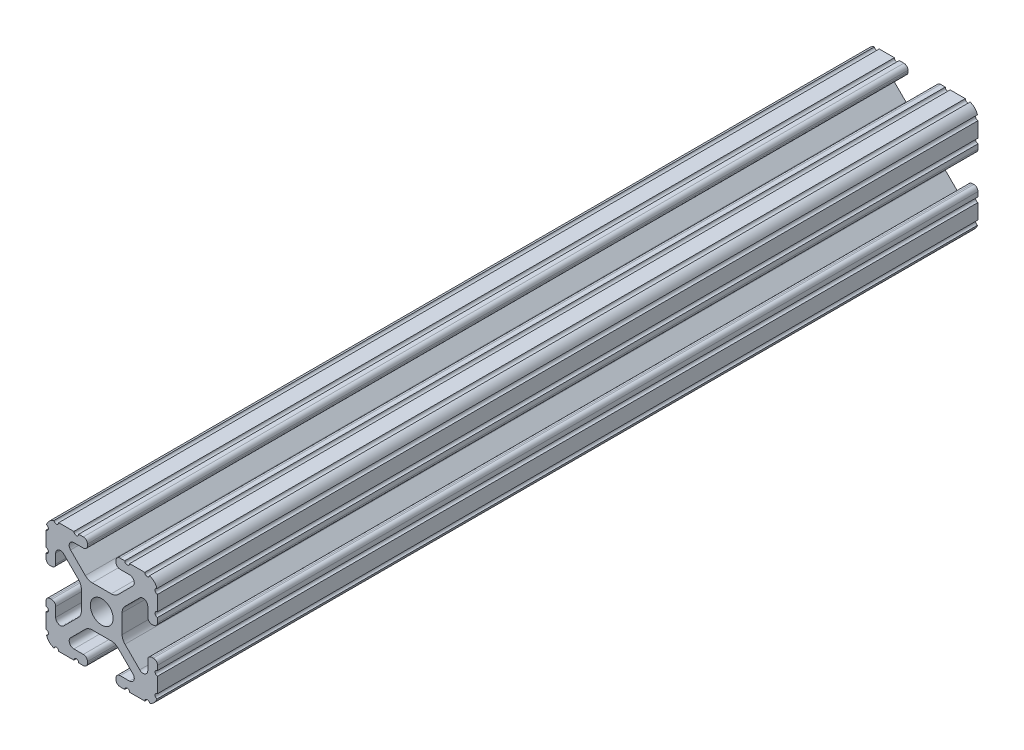
SolidWorks part; units mm, degrees
ref_plane "Front Plane" through (0, 0, 0) normal (0, 0, 1) x (1, 0, 0)
ref_plane "Top Plane" through (0, 0, 0) normal (0, 1, 0) x (1, 0, 0)
ref_plane "Right Plane" through (0, 0, 0) normal (1, 0, 0) x (0, 0, -1)
sketch "Sketch2" plane through (0, 0, 0) normal (0, 0, 1) x (1, 0, 0)
  line L0 (0, 12.7) -> (0, -12.7) construction
  line L1 (-12.7, 0) -> (12.7, 0) construction
  line L2 (3.2512, -12.7) -> (12.7, -12.7)
  line L3 (12.7, -12.7) -> (12.7, -3.2512)
  line L4 (3.2512, -12.7) -> (3.2512, -10.4902)
  line L5 (3.2512, -10.4902) -> (8.9276, -10.4902)
  line L6 (8.9276, -10.4902) -> (3.0856, -4.6482)
  line L7 (0, 0) -> (12.7, -12.7) construction
  line L8 (12.7, -3.2512) -> (10.4902, -3.2512)
  line L9 (10.4902, -3.2512) -> (10.4902, -8.9276)
  line L10 (10.4902, -8.9276) -> (4.6482, -3.0856)
  circle A0 centre (0, 0) radius 2.6035
  arc A1 (6.3485, -10.4902) -> (7.1039, -8.6665) centre (6.3485, -9.4219) ccw construction
  point P8 (0, -4.6482)
  dimension "Center Hole Diameter" = 5.207
  dimension "Rail Height" = 25.4
  dimension "Rail Width" = 25.4
  dimension "T-Slot Width" = 6.5024
  dimension "Slot Inner Width" = 14.8336
  dimension "Thickness" = 2.2098
  dimension "Slot Depth" = 5.842
  dimension "D1" = 2.2098
sketch "Sketch3" plane through (0, 0, 0) normal (1, 0, 0) x (0, 0, -1)
  line L0 (-93.4845, -12.7) -> (93.4845, -12.7) construction
  line L1 (-68.0845, 0) -> (68.0845, 0) construction
  line L2 (93.4845, 0) -> (-93.4845, 0) construction
sketch "Sketch4" plane through (0, 0, 0) normal (0, 0, 1) x (1, 0, 0)
  line L0 (4.1904, -12.7) -> (10.1173, -12.7)
  line L1 (3.2512, -12.7) -> (12.7, -12.7) construction
  line L2 (3.2512, -12.7) -> (3.2512, -10.4902) construction
  line L3 (3.2512, -10.4902) -> (8.9276, -10.4902) construction
  line L4 (3.2512, -11.4294) -> (3.2512, -11.7608)
  line L5 (4.1904, -10.4902) -> (6.3485, -10.4902)
  line L6 (0, -4.6482) -> (2.164, -4.6482)
  line L7 (8.9276, -10.4902) -> (3.0856, -4.6482) construction
  line L8 (3.7373, -5.2999) -> (7.1039, -8.6665)
  line L9 (12.7, -12.7) -> (12.7, -3.2512) construction
  line L10 (10.4902, -8.9276) -> (4.6482, -3.0856) construction
  line L11 (10.4902, -3.2512) -> (10.4902, -8.9276) construction
  line L12 (10.4902, -6.3485) -> (10.4902, -4.1904)
  line L13 (12.7, -3.2512) -> (10.4902, -3.2512) construction
  line L14 (11.4294, -3.2512) -> (11.7608, -3.2512)
  line L15 (12.7, -4.1904) -> (12.7, -10.1173)
  line L16 (8.6665, -7.1039) -> (5.2999, -3.7373)
  line L17 (4.6482, 0) -> (4.6482, -2.164)
  line L18 (-12.7, 0) -> (12.7, 0) construction
  line L19 (0, -4.6482) -> (0, -2.6035)
  line L20 (0, 12.7) -> (0, -12.7) construction
  line L21 (4.6482, 0) -> (2.6035, 0)
  arc A0 (3.2512, -11.7608) -> (4.1904, -12.7) centre (4.1904, -11.7608) ccw
  arc A2 (3.2512, -11.4294) -> (4.1904, -10.4902) centre (4.1904, -11.4294) cw
  arc A3 (6.3485, -10.4902) -> (7.1039, -8.6665) centre (6.3485, -9.4219) ccw
  arc A4 (2.164, -4.6482) -> (3.7373, -5.2999) centre (2.164, -6.8732) cw
  arc A5 (10.1173, -12.7) -> (12.7, -10.1173) centre (10.1173, -10.1173) ccw
  arc A6 (8.6665, -7.1039) -> (10.4902, -6.3485) centre (9.4219, -6.3485) ccw
  arc A7 (10.4902, -4.1904) -> (11.4294, -3.2512) centre (11.4294, -4.1904) cw
  arc A8 (11.7608, -3.2512) -> (12.7, -4.1904) centre (11.7608, -4.1904) cw
  arc A9 (5.2999, -3.7373) -> (4.6482, -2.164) centre (6.8732, -2.164) cw
  circle A10 centre (0, 0) radius 2.6035 construction
  arc A11 (0, -2.6035) -> (2.6035, 0) centre (0, 0) ccw
  dimension "D1" = 2.5827
  dimension "D2" = 2.225
  dimension "D3" = 0.9392
extrude "Boss-Extrude1" add sketch "Sketch4" along normal up to vertex (93.4845 mm away) from vertex at -93.4845 starting at point (0, -12.7, -93.4845)
sketch "Sketch5" plane through (0, 0, 0) normal (0, 0, 1) x (1, 0, 0)
  line L0 (3.2512, -12.7) -> (12.7, -12.7) construction
  line L1 (4.1904, -10.4902) -> (6.3485, -10.4902) construction
  line L3 (0, 0) -> (12.7, -12.7) construction
  line L4 (6.3485, -10.4902) -> (6.3485, -12.7) construction
  line L5 (8.9276, -10.4902) -> (3.0856, -4.6482) construction
  circle A0 centre (10.3562, -12.7) radius 0.5524
  circle A1 centre (5.796, -12.7) radius 0.5524
  circle A2 centre (12.7, -10.3562) radius 0.5524
  circle A3 centre (12.7, -5.796) radius 0.5524
  point P10 (5.2694, -10.4902)
  point P12 (9.4219, -6.3485)
  dimension "D1" = 1.1049
extrude "Cut-Extrude1" cut sketch "Sketch5" against normal through all both and the other way through all
mirror "Mirror1" about plane through (0, 0, 0) normal (1, 0, 0) of bodies 137 134
mirror "Mirror2" about plane through (0, 0, 0) normal (0, 1, 0) of bodies 135
equation "\"D1@Sketch2\"=\"Thickness@Sketch2\""
equation "\"D2@Sketch4\"=\"Slot Inner Width@Sketch2\"*0.15"
equation "\"D1@Sketch4\"=\"D3@Sketch4\"*2.75"
equation "\"D3@Sketch4\"=\"Thickness@Sketch2\"*0.425"
equation "\"D1@Sketch5\"=\"Thickness@Sketch2\"*0.5"
equation "\"D1@Boss-Extrude1\"=\"Length@Sketch3\""
